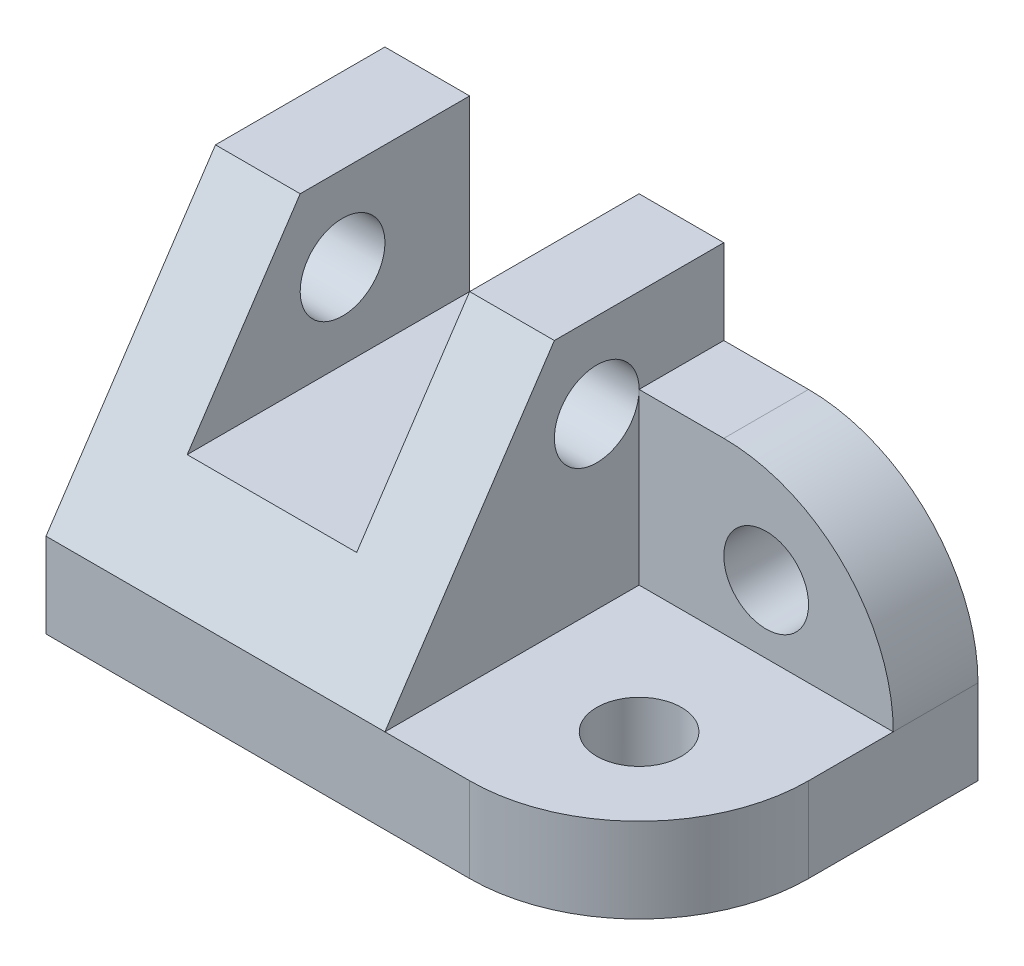
SolidWorks part; units mm, degrees
ref_plane "Front Plane" through (0, 0, 0) normal (0, 0, 1) x (1, 0, 0)
ref_plane "Top Plane" through (0, 0, 0) normal (0, 1, 0) x (1, 0, 0)
ref_plane "Right Plane" through (0, 0, 0) normal (1, 0, 0) x (0, 0, -1)
sketch "Sketch1" plane through (0, 0, 0) normal (1, 0, 0) x (0, 0, -1)
  line L0 (0, 0) -> (400, 0)
  line L1 (0, 0) -> (0, 400)
  line L2 (0, 400) -> (400, 400)
  line L3 (400, 400) -> (400, 0)
  dimension "D1" = 400
  dimension "D2" = 400
extrude "Boss-Extrude1" add sketch "Sketch1" against normal blind 700
sketch "Sketch2" plane through (0, 0, 0) normal (1, 0, 0) x (0, 0, -1)
  line L0 (0, 400) -> (0, 100)
  line L1 (0, 400) -> (0, 0) construction
  line L2 (0, 400) -> (200, 400)
  line L3 (400, 400) -> (0, 400) construction
  line L4 (0, 100) -> (200, 400)
extrude "Cut-Extrude1" cut sketch "Sketch2" against normal blind 700
sketch "Sketch4" plane through (0, 0, -400) normal (0, 0, -1) x (-1, 0, 0)
  line L1 (700, 400) -> (0, 400) construction
  line L2 (600, 400) -> (600, 200)
  line L3 (600, 200) -> (400, 200)
  line L4 (400, 200) -> (400, 400)
  line L5 (400, 400) -> (600, 400)
  dimension "D1" = 200
extrude "Cut-Extrude2" cut sketch "Sketch4" against normal blind 700
sketch "Sketch5" plane through (0, 0, 0) normal (1, 0, 0) x (0, 0, -1)
  line L0 (0, 100) -> (300, 100)
  line L1 (300, 100) -> (300, 300)
  line L2 (300, 300) -> (400, 300)
  line L3 (400, 0) -> (400, 400) construction
  line L4 (400, 300) -> (400, 400)
  line L5 (400, 400) -> (200, 400)
  line L6 (200, 400) -> (0, 100)
  dimension "D1" = 300
  dimension "D2" = 200
  dimension "D3" = 100
  dimension "D4" = 200
extrude "Cut-Extrude3" cut sketch "Sketch5" against normal blind 300
fillet "Fillet1" radius 200 2 edges at (0, 200, -300) (0, 300, -350)
sketch "Sketch6" plane through (0, 100, 0) normal (0, 1, 0) x (1, 0, 0)
  circle A0 centre (-150, 150) radius 50
extrude "Cut-Extrude4" cut sketch "Sketch6" against normal blind 300
fillet "Fillet2" radius 200 1 edges at (0, 50, 0)
sketch "Sketch7" plane through (0, 0, -300) normal (0, 0, 1) x (1, 0, 0)
  circle A0 centre (-150, 180) radius 50
extrude "Cut-Extrude5" cut sketch "Sketch7" against normal blind 228
sketch "Sketch8" plane through (-700, 0, 0) normal (-1, 0, 0) x (0, 0, 1)
  circle A0 centre (-250, 300) radius 50
extrude "Cut-Extrude6" cut sketch "Sketch8" against normal blind 708
